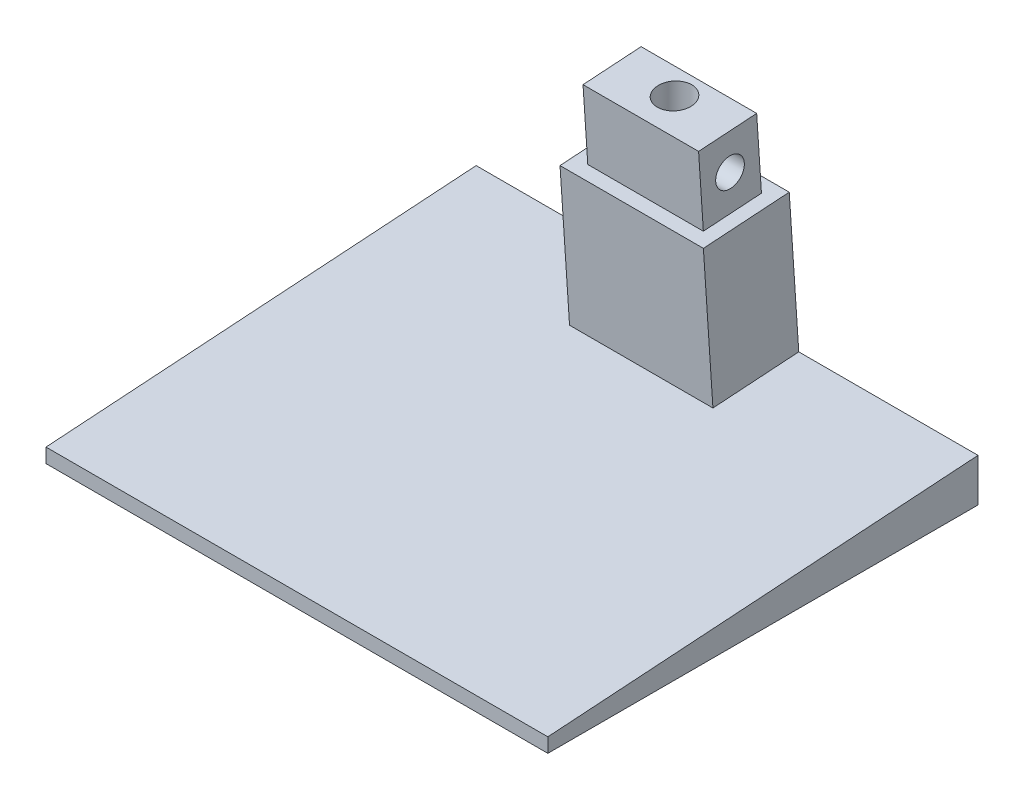
SolidWorks part; units mm, degrees
ref_plane "Front Plane" through (0, 0, 0) normal (0, 0, 1) x (1, 0, 0)
ref_plane "Top Plane" through (0, 0, 0) normal (0, 1, 0) x (1, 0, 0)
ref_plane "Right Plane" through (0, 0, 0) normal (1, 0, 0) x (0, 0, -1)
sketch "Sketch1" plane through (0, 0, 0) normal (0, 1, 0) x (1, 0, 0)
  line L1 (0, 0) -> (175, 0)
  line L2 (0, 0) -> (0, 150)
  line L3 (0, 150) -> (175, 150)
  line L4 (175, 0) -> (175, 150)
  dimension "D1" = 175
  dimension "D2" = 150
extrude "Boss-Extrude1" add sketch "Sketch1" along normal blind 15
sketch "Sketch2" plane through (175, 0, 0) normal (1, 0, 0) x (0, 0, -1)
  line L0 (150, 15) -> (0, 5)
  line L1 (0, 15) -> (0, 0) construction
  line L2 (150, 15) -> (0, 15)
  line L3 (0, 15) -> (0, 5)
  dimension "D1" = 5
extrude "Cut-Extrude1" cut sketch "Sketch2" against normal through all
sketch "Sketch3" plane through (0, 4.9779, 0.3319) normal (0, 0.9978, 0.0665) x (1, 0, 0)
  line L0 (175, 150.6656) -> (0, 150.6656) construction
  line L1 (62.5, 150.6656) -> (112.5, 150.6656)
  line L2 (62.5, 150.6656) -> (62.5, 120.6656)
  line L3 (62.5, 120.6656) -> (112.5, 120.6656)
  line L4 (112.5, 150.6656) -> (112.5, 120.6656)
  line L5 (0, 0.3326) -> (0, 150.6656) construction
  dimension "D1" = 30
  dimension "D2" = 50
  dimension "D3" = 62.5
extrude "Boss-Extrude2" add sketch "Sketch3" along normal blind 50
sketch "Sketch4" plane through (0, 54.8671, 3.6578) normal (0, 0.9978, 0.0665) x (1, 0, 0)
  line L0 (62.5, 120.6656) -> (112.5, 120.6656) construction
  line L1 (67.35, 145.8156) -> (107.65, 145.8156)
  line L2 (67.35, 145.8156) -> (67.35, 125.5156)
  line L3 (67.35, 125.5156) -> (107.65, 125.5156)
  line L4 (107.65, 145.8156) -> (107.65, 125.5156)
  line L5 (112.5, 120.6656) -> (112.5, 150.6656) construction
  line L6 (62.5, 150.6656) -> (62.5, 120.6656) construction
  line L7 (112.5, 150.6656) -> (62.5, 150.6656) construction
  dimension "D1" = 4.85
  dimension "D2" = 4.85
  dimension "D3" = 4.85
  dimension "D4" = 4.85
extrude "Boss-Extrude3" add sketch "Sketch4" along normal blind 25
sketch "Sketch5" plane through (67.35, 0, 0) normal (-1, 0, 0) x (0, 0, 1)
  line L0 (-116.7405, 62.8937) -> (-120.0664, 13.0044) construction
  line L1 (-141.8348, 64.5666) -> (-121.5798, 63.2163) construction
  circle A0 centre (-130.8758, 76.3638) radius 5
  dimension "D1" = 10
  dimension "D2" = 15
  dimension "D3" = 12.5
extrude "Cut-Extrude3" cut sketch "Sketch5" against normal through all
sketch "Sketch7" plane through (0, 0, 0) normal (0, -1, 0) x (1, 0, 0)
  line L1 (112.5, -146.674) -> (112.5, -150) construction
  circle A0 centre (87.5, -131.674) radius 6
  dimension "D1" = 12
  dimension "D2" = 15
  dimension "D3" = 25
extrude "Cut-Extrude5" cut sketch "Sketch7" against normal through all
sketch "Sketch8" plane through (0, 0, 0) normal (0, -1, 0) x (1, 0, 0)
  circle A0 centre (87.5, -131.674) radius 12.5
  dimension "D1" = 25
extrude "Cut-Extrude6" cut sketch "Sketch8" against normal blind 12.5
